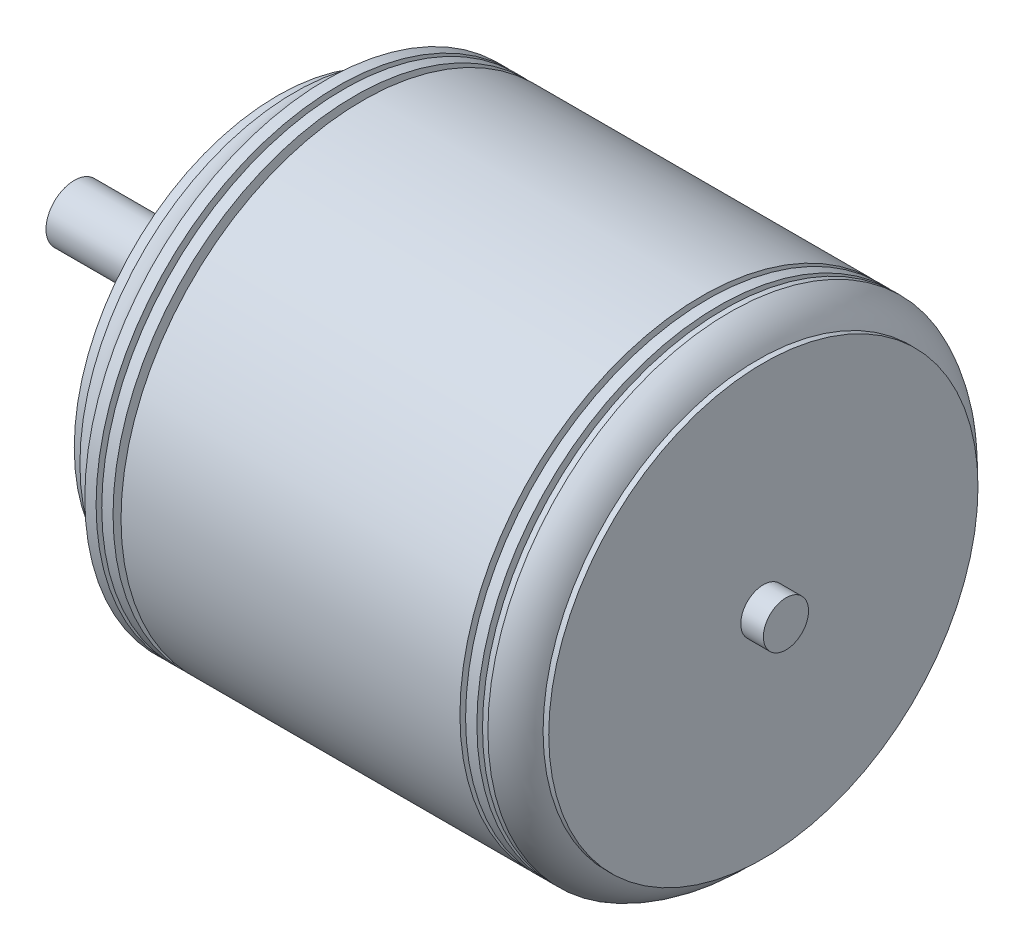
SolidWorks part; units mm, degrees
ref_plane "Front Plane" through (0, 0, 0) normal (0, 0, 1) x (1, 0, 0)
ref_plane "Top Plane" through (0, 0, 0) normal (0, 1, 0) x (1, 0, 0)
ref_plane "Right Plane" through (0, 0, 0) normal (1, 0, 0) x (0, 0, -1)
sketch "Sketch6" plane through (0, 0, 0) normal (0, 0, 1) x (1, 0, 0)
  line L0 (0, 0) -> (200, 0)
  line L1 (200, 0) -> (200, 2)
  line L2 (200, 2) -> (198, 2)
  line L4 (200, 0) -> (155, 0)
  line L5 (155, 2.5) -> (155, 18)
  line L6 (159.3325, 21.4) -> (160.3325, 21.4)
  line L8 (159.3325, 21.4) -> (160.3325, 21.4)
  line L9 (160.3325, 21.4) -> (160.3325, 20.4)
  line L10 (160.3325, 20.4) -> (160.8325, 20.4)
  line L11 (160.8325, 20.4) -> (160.8325, 21.4)
  line L12 (160.8325, 21.4) -> (161.8325, 21.4)
  line L13 (161.8325, 21.4) -> (161.8325, 0)
  line L14 (161.8325, 13.9827) -> (162.5396, 13.2756)
  line L15 (162.5396, 13.2756) -> (162.5396, 0)
  line L16 (162.5396, 13.2756) -> (162.5396, 21.4)
  line L17 (162.5396, 21.4) -> (192.5396, 21.4)
  line L18 (192.5396, 21.4) -> (192.5396, 20.4)
  line L19 (192.5396, 20.4) -> (193.0396, 20.4)
  line L20 (193.0396, 20.4) -> (193.0396, 21.4)
  line L21 (193.0396, 21.4) -> (194.0396, 21.4)
  line L22 (194.0396, 21.4) -> (194.0396, 20.4)
  line L23 (194.0396, 20.4) -> (194.5396, 20.4)
  line L24 (194.5396, 20.4) -> (194.5396, 21.4)
  line L25 (194.5396, 21.4) -> (195.0162, 21.4)
  line L26 (193.0396, 21.4) -> (194.0396, 21.4)
  line L27 (162.5396, 21.4) -> (192.5396, 21.4)
  line L28 (160.8325, 21.4) -> (161.8325, 21.4)
  line L29 (198, 2) -> (198, 19)
  line L30 (198, 19) -> (197.5, 19)
  line L31 (156.5, 19) -> (156.5, 18)
  line L32 (156.5, 18) -> (155, 18)
  line L33 (155, 2.5) -> (137, 2.5)
  line L34 (137, 2.5) -> (137, 0)
  arc A1 (156.5, 19) -> (159.3325, 21.4) centre (154.9553, 23.6946) ccw
  arc A2 (195.0162, 21.4) -> (197.5, 19) centre (193.3706, 17.2117) cw
  dimension "D3" = 2
  dimension "D8" = 1
  dimension "D20" = 0.5
  dimension "D21" = 4.5
  dimension "D1" = 200
  dimension "D2" = 2
  dimension "D4" = 17
  dimension "D5" = 45
  dimension "D6" = 0.5
  dimension "D9" = 1
  dimension "D10" = 0.5
  dimension "D11" = 1
  dimension "D12" = 1
  dimension "D13" = 1
  dimension "D14" = 30
  dimension "D15" = 1
  dimension "D16" = 0.5
  dimension "D17" = 1
  dimension "D18" = 1
  dimension "D19" = 1
  dimension "D22" = 1
revolve "Revolve1" add sketch "Sketch6" angle 360 about L0
